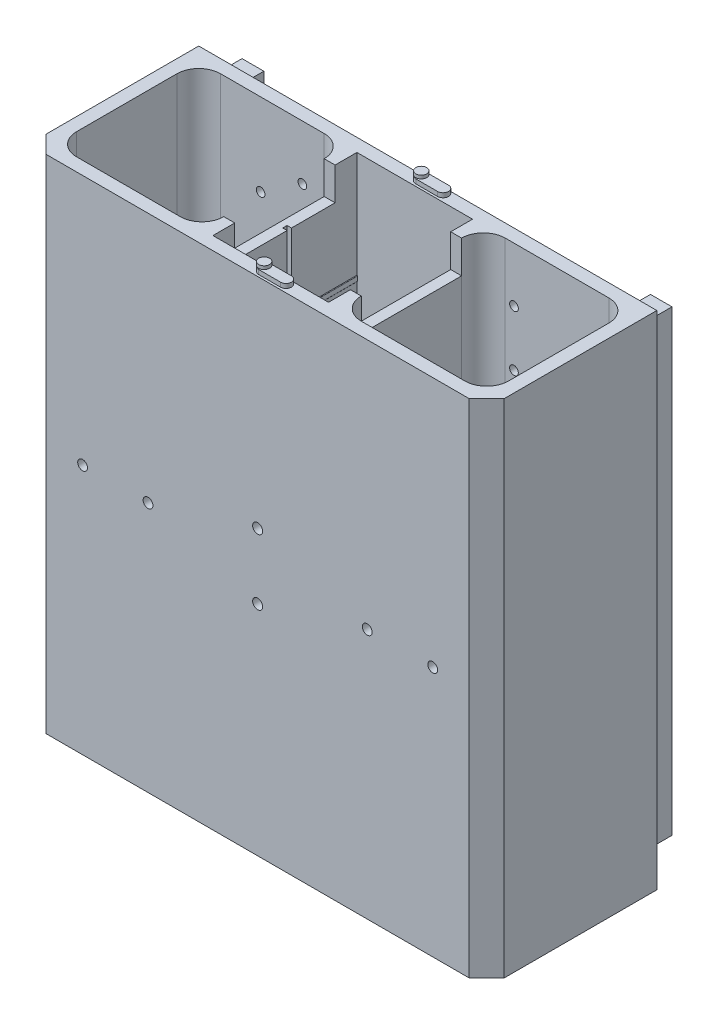
SolidWorks part; units mm, degrees
ref_plane "前视基准面" through (0, 0, 0) normal (0, 0, 1) x (1, 0, 0)
ref_plane "上视基准面" through (0, 0, 0) normal (0, 1, 0) x (1, 0, 0)
ref_plane "右视基准面" through (0, 0, 0) normal (1, 0, 0) x (0, 0, -1)
other "Configuration Table"
sketch "草图1" plane through (0, 0, 0) normal (0, 0, 1) x (1, 0, 0)
  line L1 (0, 0) -> (210, 0)
  line L2 (0, 0) -> (0, 230)
  line L3 (0, 230) -> (210, 230)
  line L4 (210, 0) -> (210, 230)
  line L5 (0, 0) -> (210, 230) construction
  line L6 (0, 230) -> (210, 0) construction
  line L7 (0, 230) -> (26, 230)
  line L8 (0, 230) -> (0, 0)
  line L9 (0, 0) -> (26, 0)
  point P4 (105, 115)
  point P8 (13, 115)
  dimension "D1" = 230
  dimension "D2" = 210
extrude "凸台-拉伸1" add sketch "草图1" along normal blind 6 contours L1 L4 L3 L2
sketch "草图2" plane through (0, 0, 0) normal (0, 0, -1) x (-1, 0, 0)
  line L0 (0, 230) -> (-210, 230) construction
  line L1 (0, 0) -> (-210, 0) construction
  line L2 (-210, 230) -> (-184, 230)
  line L3 (-210, 230) -> (-210, 0)
  line L4 (-210, 0) -> (-184, 0)
  line L5 (-184, 230) -> (-184, 0) construction
  line L6 (-210, 230) -> (-184, 0) construction
  line L7 (-210, 0) -> (-184, 230) construction
  line L9 (0, 230) -> (-20, 230)
  line L10 (0, 230) -> (0, 0)
  line L11 (0, 0) -> (-20, 0)
  line L13 (0, 230) -> (-20, 0) construction
  line L14 (0, 0) -> (-20, 230) construction
  line L15 (-201.925, 219.925) -> (-192.075, 219.925)
  line L16 (-201.925, 219.925) -> (-201.925, 10.075)
  line L17 (-201.925, 10.075) -> (-192.075, 10.075)
  line L18 (-192.075, 219.925) -> (-192.075, 10.075)
  line L19 (-201.925, 219.925) -> (-192.075, 10.075) construction
  line L20 (-201.925, 10.075) -> (-192.075, 219.925) construction
  line L21 (-14.85, 219.925) -> (-4.85, 219.925)
  line L22 (-14.85, 219.925) -> (-14.85, 10.075)
  line L23 (-14.85, 10.075) -> (-4.85, 10.075)
  line L24 (-4.85, 219.925) -> (-4.85, 10.075)
  line L25 (-14.85, 219.925) -> (-4.85, 10.075) construction
  line L26 (-14.85, 10.075) -> (-4.85, 219.925) construction
  point P6 (-197, 115)
  point P18 (-197, 115)
  point P23 (-9.85, 115)
  dimension "D1" = 26
  dimension "D2" = 20
  dimension "D3" = 209.85
  dimension "D4" = 9.85
  dimension "D5" = 13
  dimension "D6" = 115
  dimension "D7" = 209.85
  dimension "D8" = 115
  dimension "D9" = 9.85
  dimension "D10" = 10
extrude "凸台-拉伸3" add sketch "草图2" along normal blind 15 contours L18 L15 L16 L17 | L24 L21 L22 L23
sketch "草图3" plane through (0, 0, 0) normal (0, 0, -1) x (-1, 0, 0)
  line L0 (0, 0) -> (-210, 0) construction
  line L1 (-210, 230) -> (-184, 230)
  line L2 (-210, 230) -> (-210, 0)
  line L3 (-210, 0) -> (-184, 0)
  line L4 (-184, 230) -> (-184, 0)
  line L5 (-210, 230) -> (-184, 0) construction
  line L6 (-210, 0) -> (-184, 230) construction
  line L7 (-210, 115) -> (119.2636, 115) construction
  line L8 (0, 230) -> (-20, 230)
  line L9 (0, 230) -> (0, 0)
  line L10 (0, 0) -> (-20, 0)
  line L11 (-20, 230) -> (-20, 0)
  line L12 (0, 230) -> (-20, 0) construction
  line L13 (0, 0) -> (-20, 230) construction
  line L14 (-105, 230) -> (-105, 0) construction
  circle A0 centre (-169.6426, 192.25) radius 2
  circle A1 centre (-150.5, 205) radius 2
  circle A2 centre (-150.5, 179.5) radius 2
  circle A3 centre (-150.5, 50.5) radius 2
  circle A4 centre (-150.5, 25) radius 2
  circle A5 centre (-169.6426, 37.75) radius 2
  circle A6 centre (-34.3574, 192.25) radius 2
  circle A7 centre (-53.5, 205) radius 2
  circle A8 centre (-53.5, 179.5) radius 2
  circle A9 centre (-53.5, 50.5) radius 2
  circle A10 centre (-53.5, 25) radius 2
  circle A11 centre (-34.3574, 37.75) radius 2
  point P4 (-197, 115)
  point P12 (-10, 115)
  dimension "D8" = 4
  dimension "D9" = 4
  dimension "D10" = 4
  dimension "D12" = 4
  dimension "D13" = 4
  dimension "D14" = 4
  dimension "D1" = 26
  dimension "D2" = 20
  dimension "D3" = 25.5
  dimension "D4" = 23
  dimension "D5" = 23
  dimension "D6" = 33.5
  dimension "D7" = 33.5
  dimension "D11" = 90
  dimension "D15" = 25.5
  dimension "D16" = 23
  dimension "D17" = 23
  dimension "D18" = 33.5
  dimension "D19" = 33.5
  dimension "D20" = 90
extrude "切除-拉伸1" cut sketch "草图3" against normal blind 10 contours A10 | A11 | A9 | A6 | A8 | A7 | A1 | A2 | A0 | A4 | A3 | A5
chamfer "倒角1" [suppressed] distance 10 angle 45
sketch "草图5" [suppressed] plane through (0, 0, 0) normal (0, 0, -1) x (-1, 0, 0)
  line L0 (-172.5, 115) -> (-135, 115) construction
  line L1 (-10, 230) -> (-200, 230) construction
  line L2 (-210, 10) -> (-210, 220) construction
  line L5 (-210, 220) -> (-210, 0)
  line L8 (-75, 115) -> (-37.5, 115) construction
  line L9 (-210, 0) -> (-184, 220) construction
  line L10 (0, 10) -> (0, 220) construction
  circle A0 centre (-172.5, 115) radius 2.5
  circle A1 centre (-135, 115) radius 2.5
  circle A2 centre (-75, 115) radius 2.5
  circle A3 centre (-37.5, 115) radius 2.5
  point P12 (-197, 110)
  dimension "D3" = 5
  dimension "D4" = 5
  dimension "D8" = 5
  dimension "D9" = 5
  dimension "D1" = 37.5
  dimension "D2" = 115
  dimension "D5" = 75
  dimension "D6" = 26
  dimension "D7" = 37.5
  dimension "D10" = 115
  dimension "D11" = 75
extrude "切除-拉伸2" [suppressed] cut sketch "草图5" against normal blind 10 contours A0 | A1 | A3 | A2
sketch "草图6" plane through (0, 0, 6) normal (0, 0, 1) x (1, 0, 0)
  line L0 (105, 230) -> (105, 0) construction
  line L3 (0, 115) -> (210, 115) construction
  line L6 (86.25, 115) -> (123.75, 115) construction
  line L7 (105, 133.75) -> (105, 96.25) construction
  circle A2 centre (105, 133.75) radius 2.5
  circle A3 centre (105, 96.25) radius 2.5
  point P7 (105, 115)
  point P11 (105, 115)
  dimension "D1" = 37.5
  dimension "D2" = 5
  dimension "D3" = 5
extrude "切除-拉伸3" [suppressed] cut sketch "草图6" against normal blind 10
sketch "草图7" [suppressed] plane through (0, 0, 18) normal (0, 0, 1) x (1, 0, 0)
  line L0 (0, 0) -> (210, 0) construction
  line L1 (0, 230) -> (6, 230)
  line L2 (0, 230) -> (0, 0)
  line L3 (0, 0) -> (6, 0)
  line L4 (6, 230) -> (6, 0)
  line L5 (0, 230) -> (6, 0) construction
  line L6 (0, 0) -> (6, 230) construction
  point P4 (3, 115)
  dimension "D1" = 6
extrude "凸台-拉伸4" [suppressed] add sketch "草图7" along normal blind 55
sketch "草图8" [suppressed] plane through (0, 0, 18) normal (0, 0, 1) x (1, 0, 0)
  line L0 (0, 0) -> (210, 0) construction
  line L1 (210, 230) -> (200.2731, 230)
  line L2 (210, 230) -> (210, 0)
  line L3 (210, 0) -> (200.2731, 0)
  line L4 (200.2731, 230) -> (200.2731, 0)
  line L5 (210, 230) -> (200.2731, 0) construction
  line L6 (210, 0) -> (200.2731, 230) construction
  point P4 (205.1365, 115)
  dimension "D1" = 9.7269
sketch "草图17" plane through (0, 0, 6) normal (0, 0, 1) x (1, 0, 0)
  line L0 (0, 0) -> (210, 0) construction
  line L1 (0, 230) -> (6, 230)
  line L2 (0, 230) -> (0, 0)
  line L3 (0, 0) -> (6, 0)
  line L4 (6, 230) -> (6, 0)
  line L5 (0, 230) -> (6, 0) construction
  line L6 (0, 0) -> (6, 230) construction
  line L8 (210, 230) -> (204, 230)
  line L9 (210, 230) -> (210, 0)
  line L10 (210, 0) -> (204, 0)
  line L11 (204, 230) -> (204, 0)
  line L12 (210, 230) -> (204, 0) construction
  line L13 (210, 0) -> (204, 230) construction
  point P4 (3, 115)
  point P12 (207, 115)
  dimension "D1" = 6
  dimension "D2" = 6
extrude "凸台-拉伸9" add sketch "草图17" along normal blind 66
ref_plane "基准面2" through (0, 0, 72) normal (0, 0, 1) x (1, 0, 0)
sketch "草图18" plane through (0, 0, 72) normal (0, 0, 1) x (1, 0, 0)
  line L0 (210, 230) -> (204, 230) construction
  line L1 (210, 0) -> (210, 230) construction
  line L2 (204, 0) -> (210, 0) construction
  line L3 (6, 0) -> (204, 0) construction
  line L4 (0, 0) -> (6, 0) construction
  line L5 (0, 230) -> (0, 0) construction
  line L6 (6, 230) -> (0, 230) construction
  line L7 (6, 230) -> (204, 230) construction
  line L8 (210, 230) -> (204, 230)
  line L9 (210, 0) -> (210, 230)
  line L10 (204, 0) -> (210, 0)
  line L11 (6, 0) -> (204, 0)
  line L12 (0, 0) -> (6, 0)
  line L13 (0, 230) -> (0, 0)
  line L14 (6, 230) -> (0, 230)
  line L15 (6, 230) -> (204, 230)
extrude "凸台-拉伸10" add sketch "草图18" along normal blind 6
chamfer "倒角3" distance 8 angle 45 2 edges at (0, 115, 78) (210, 115, 78)
sketch "草图19" plane through (0, 0, 72) normal (0, 0, -1) x (-1, 0, 0)
  line L0 (-105, 230) -> (-105, 0) construction
  line L2 (-131.5, 230) -> (-136.5, 230)
  line L3 (0, 230) -> (-210, 230) construction
  line L4 (0, 0) -> (-210, 0) construction
  line L5 (-131.5, 230) -> (-131.5, 0)
  line L6 (-131.5, 230) -> (-78.5, 230)
  line L7 (-131.5, 230) -> (-131.5, 0)
  line L8 (-131.5, 0) -> (-78.5, 0)
  line L9 (-78.5, 230) -> (-78.5, 0)
  line L10 (-131.5, 230) -> (-78.5, 0) construction
  line L11 (-131.5, 0) -> (-78.5, 230) construction
  line L12 (-131.5, 0) -> (-136.5, 0)
  line L13 (-136.5, 230) -> (-136.5, 0)
  line L14 (-131.5, 230) -> (-136.5, 0) construction
  line L15 (-131.5, 0) -> (-136.5, 230) construction
  line L16 (-78.5, 230) -> (-73.5, 230)
  line L17 (-78.5, 230) -> (-78.5, 0)
  line L18 (-78.5, 0) -> (-73.5, 0)
  line L19 (-73.5, 230) -> (-73.5, 0)
  line L20 (-78.5, 230) -> (-73.5, 0) construction
  line L21 (-78.5, 0) -> (-73.5, 230) construction
  point P10 (-105, 115)
  point P13 (-134, 115)
  point P16 (-76, 115)
  dimension "D1" = 53
  dimension "D2" = 0
  dimension "D3" = 5
  dimension "D4" = 5
extrude "凸台-拉伸11" add sketch "草图19" along normal blind 66 contours L19 L7 L9 L4 | L7 L13 L4 L5
fillet "圆角4" radius 10 8 edges at (136.5, 115, 72) (136.5, 115, 6) (204, 115, 6) (204, 115, 72) (73.5, 115, 6) (73.5, 115, 72) (6, 115, 6) (6, 115, 72)
sketch "草图21" plane through (0, 0, 72) normal (0, 0, 1) x (1, 0, 0)
  line L0 (8, 115) -> (202, 115) construction
  line L1 (8, 230) -> (8, 0) construction
  line L2 (202, 0) -> (202, 230) construction
  line L3 (105, 230) -> (105, 0) construction
  line L4 (202, 230) -> (8, 230) construction
  line L5 (8, 0) -> (202, 0) construction
  line L6 (105, 130) -> (105, 100) construction
  circle A0 centre (105, 130) radius 2.3
  circle A1 centre (105, 100) radius 2.3
  point P14 (105, 115)
  dimension "D3" = 4.6
  dimension "D4" = 4.6
  dimension "D1" = 0
  dimension "D2" = 30
extrude "切除-拉伸9" cut sketch "草图21" along normal blind 6 contours A1 | A0
sketch "草图23" plane through (78.5, 0, 0) normal (1, 0, 0) x (0, 0, -1)
  line L0 (-6, 80) -> (-70, 80)
  line L1 (-6, 230) -> (-70, 230) construction
  line L2 (-6, 230) -> (-6, 0) construction
  line L3 (-6, 0) -> (-70, 0) construction
  line L4 (-70, 230) -> (-70, 0) construction
  line L5 (-6, 230) -> (-70, 0) construction
  line L6 (-6, 0) -> (-70, 230) construction
  line L7 (-6, 230) -> (-70, 230)
  line L8 (-6, 230) -> (-6, 40)
  line L9 (-6, 40) -> (-70, 40)
  line L10 (-70, 230) -> (-70, 40)
  line L11 (-6, 230) -> (-70, 40) construction
  line L12 (-6, 40) -> (-70, 230) construction
  point P4 (-38, 115)
  point P9 (-38, 135)
  dimension "D1" = 190
  dimension "D2" = 40
sketch "草图24" plane through (0, 0, 6) normal (0, 0, 1) x (1, 0, 0)
  line L0 (78.5, 80.5) -> (78.5, 79.5) construction
  line L1 (78.5, 230) -> (78.5, 40) construction
  line L2 (80, 80.5) -> (80, 79.5)
  line L4 (78.5, 82) -> (78.5, 78)
  arc A0 (80, 80.5) -> (78.5, 82) centre (78.5, 80.5) ccw
  arc A1 (78.5, 78) -> (80, 79.5) centre (78.5, 79.5) ccw
  point P0 (78.5, 80)
  point P6 (78.5, 80)
  dimension "D3" = 1.5
  dimension "D4" = 1.5
  dimension "D1" = 0
  dimension "D2" = 1
extrude "凸台-拉伸12" [suppressed] add sketch "草图24" along normal blind 66
ref_plane "基准面3" through (105, 0, 0) normal (-1, 0, 0) x (0, 0, 1)
mirror "镜向1" [suppressed] about plane through (105, 0, 0) normal (-1, 0, 0)
sketch "草图25" plane through (0, 0, 72) normal (0, 0, -1) x (-1, 0, 0)
  line L8 (-131.5, 230) -> (-131.5, 0)
  line L11 (-131.5, 0) -> (-78.5, 0)
  line L12 (-78.5, 0) -> (-78.5, 230)
  line L15 (-78.5, 230) -> (-131.5, 230)
  line L16 (-131.5, 230) -> (-131.5, 0)
  line L19 (-131.5, 0) -> (-78.5, 0)
  line L20 (-78.5, 0) -> (-78.5, 230)
  line L23 (-78.5, 230) -> (-131.5, 230)
  dimension "D1" = 0
sketch "草图26" plane through (0, 0, 72) normal (0, 0, -1) x (-1, 0, 0)
  line L0 (-131.5, 181) -> (-131.5, 179) construction
  line L1 (-131.5, 230) -> (-131.5, 0) construction
  line L2 (-131.26, 181) -> (-131.26, 179)
  line L3 (-131.74, 181) -> (-131.74, 179)
  line L4 (-78.5, 230) -> (-131.5, 230) construction
  line L5 (-131.5, 230) -> (-131.5, 0) construction
  line L6 (-78.5, 230) -> (-131.5, 230) construction
  line L7 (-131.5, 22.5) -> (-131.5, 20.5) construction
  line L8 (-131.26, 22.5) -> (-131.26, 20.5)
  line L9 (-131.74, 22.5) -> (-131.74, 20.5)
  arc A0 (-131.26, 181) -> (-131.74, 181) centre (-131.5, 181) ccw
  arc A1 (-131.74, 179) -> (-131.26, 179) centre (-131.5, 179) ccw
  arc A2 (-131.26, 22.5) -> (-131.74, 22.5) centre (-131.5, 22.5) ccw
  arc A3 (-131.74, 20.5) -> (-131.26, 20.5) centre (-131.5, 20.5) ccw
  point P4 (-131.5, 180)
  point P14 (-131.5, 21.5)
  dimension "D1" = 0.24
  dimension "D2" = 2
  dimension "D3" = 50
  dimension "D4" = 2
extrude "凸台-拉伸13" add sketch "草图26" along normal blind 66
mirror "镜向2" about plane through (105, 0, 0) normal (-1, 0, 0) of "凸台-拉伸13"
sketch "草图28" plane through (0, 0, 72) normal (0, 0, -1) x (-1, 0, 0)
  line L0 (-78.5, 230) -> (-131.5, 230) construction
  line L1 (-78.5, 230) -> (-131.5, 230) construction
  line L2 (-131.5, 230) -> (-131.5, 0) construction
  line L3 (-131.5, 11.46) -> (-78.5, 11.46)
  line L4 (-131.5, 11.46) -> (-131.5, 8.46)
  line L5 (-131.5, 8.46) -> (-78.5, 8.46)
  line L6 (-78.5, 11.46) -> (-78.5, 8.46)
  line L7 (-131.5, 11.46) -> (-78.5, 8.46) construction
  line L8 (-131.5, 8.46) -> (-78.5, 11.46) construction
  line L9 (-78.5, 230) -> (-78.5, 0) construction
  point P6 (-105, 9.96)
  point P11 (-78.5, 20.2624)
  dimension "D1" = 218.54
  dimension "D2" = 3
extrude "凸台-拉伸14" add sketch "草图28" along normal blind 66
sketch "草图30" plane through (0, 230, 0) normal (0, 1, 0) x (1, 0, 0)
  line L0 (78.5, -6) -> (131.5, -6) construction
  line L1 (78.5, -6) -> (131.5, -6) construction
  line L2 (78.5, -6) -> (78.5, -70) construction
  line L3 (78.5, -36) -> (76.5, -36)
  line L4 (78.5, -36) -> (78.5, -38)
  line L5 (78.5, -38) -> (76.5, -38)
  line L6 (76.5, -36) -> (76.5, -38)
  line L7 (78.5, -36) -> (76.5, -38) construction
  line L8 (78.5, -38) -> (76.5, -36) construction
  point P6 (77.5, -37)
  dimension "D1" = 2
  dimension "D2" = 30
  dimension "D3" = 2
extrude "切除-拉伸10" cut sketch "草图30" against normal blind 35
sketch "草图31" plane through (0, 8.46, 0) normal (0, -1, 0) x (1, 0, 0)
  line L0 (105, 72) -> (105, 6) construction
  line L1 (105, 16.2) -> (117.5, 16.2) construction
  line L2 (98, 23.2) -> (112, 23.2)
  line L3 (98, 23.2) -> (98, 9.2)
  line L4 (131.5, 72) -> (78.5, 72)
  line L5 (78.5, 72) -> (78.5, 6)
  line L6 (78.5, 6) -> (131.5, 6)
  line L7 (131.5, 6) -> (131.5, 72)
  line L8 (131.5, 72) -> (78.5, 72) construction
  line L9 (78.5, 72) -> (78.5, 6) construction
  line L10 (78.5, 6) -> (131.5, 6) construction
  line L11 (131.5, 6) -> (131.5, 72) construction
  line L12 (98, 9.2) -> (112, 9.2)
  line L13 (112, 23.2) -> (112, 9.2)
  line L14 (98, 23.2) -> (112, 9.2) construction
  line L15 (98, 9.2) -> (112, 23.2) construction
  circle A0 centre (92.7, 16.2) radius 1.35
  circle A1 centre (117.3, 16.2) radius 1.35
  point P10 (105, 16.2)
  dimension "D8" = 2.7
  dimension "D9" = 2.7
  dimension "D2" = 14
  dimension "D3" = 14
  dimension "D4" = 12.3
  dimension "D5" = 12.3
  dimension "D6" = 3.2
  dimension "D7" = 0
  dimension "D1" = 0
extrude "切除-拉伸11" cut sketch "草图31" against normal through all
sketch "草图32" plane through (0, 0, 6) normal (0, 0, 1) x (1, 0, 0)
  line L0 (131.5, 8.46) -> (78.5, 8.46) construction
  line L1 (119.5, 8.46) -> (131.5, 8.46)
  line L2 (119.5, 8.46) -> (119.5, -1.54)
  line L3 (119.5, -1.54) -> (131.5, -1.54)
  line L4 (131.5, 8.46) -> (131.5, -1.54)
  line L5 (119.5, 8.46) -> (131.5, -1.54) construction
  line L6 (119.5, -1.54) -> (131.5, 8.46) construction
  line L7 (131.5, 8.46) -> (78.5, 8.46) construction
  line L8 (131.5, 8.46) -> (131.5, 0) construction
  line L9 (131.5, 8.46) -> (131.5, 0) construction
  line L10 (78.5, 0) -> (131.5, 0) construction
  line L11 (78.5, 0) -> (131.5, 0) construction
  point P4 (125.5, 3.46)
  dimension "D1" = 10
  dimension "D2" = 0
  dimension "D3" = 0
  dimension "D4" = 12
extrude "切除-拉伸12" cut sketch "草图32" against normal through all
sketch "草图33" plane through (131.5, 0, 0) normal (-1, 0, 0) x (0, 0, 1)
  line L0 (0, 8.46) -> (72, 8.46) construction
  line L1 (30, 8.46) -> (50, 8.46)
  line L2 (30, 8.46) -> (30, 0)
  line L3 (30, 0) -> (50, 0)
  line L4 (50, 8.46) -> (50, 0)
  line L5 (30, 8.46) -> (50, 0) construction
  line L6 (30, 0) -> (50, 8.46) construction
  line L7 (0, 0) -> (72, 0) construction
  line L8 (0, 0) -> (0, 8.46) construction
  point P4 (40, 4.23)
  point P9 (30, 4.23)
  dimension "D1" = 20
  dimension "D2" = 30
extrude "切除-拉伸13" cut sketch "草图33" against normal up to next
sketch "草图34" plane through (0, 0, 72) normal (0, 0, -1) x (-1, 0, 0)
  line L0 (-170.25, 230) -> (-170.25, 0) construction
  line L1 (-194, 115) -> (-146.5, 115) construction
  line L2 (-185.25, 115) -> (-155.25, 115)
  line L4 (-194, 0) -> (-146.5, 0)
  line L19 (-194, 0) -> (-146.5, 0)
  line L23 (-146.5, 0) -> (-146.5, 230)
  line L25 (-146.5, 0) -> (-146.5, 230)
  line L27 (-146.5, 230) -> (-194, 230)
  line L28 (-146.5, 230) -> (-194, 230)
  line L29 (-194, 230) -> (-194, 0)
  line L30 (-194, 230) -> (-194, 0)
  circle A0 centre (-185.25, 115) radius 2.25
  circle A1 centre (-155.25, 115) radius 2.25
  point P12 (-170.25, 115)
  dimension "D2" = 4.5
  dimension "D3" = 4.5
  dimension "D4" = 30
  dimension "D1" = 0
extrude "切除-拉伸14" cut sketch "草图34" against normal blind 30 contours A0 | A1
sketch "草图36" plane through (0, 0, 72) normal (0, 0, -1) x (-1, 0, 0)
  line L0 (-39.75, 230) -> (-39.75, 0) construction
  line L1 (-63.5, 115) -> (-16, 115) construction
  line L2 (-54.75, 115) -> (-24.75, 115)
  line L4 (-16, 230) -> (-63.5, 230)
  line L19 (-16, 230) -> (-63.5, 230)
  line L23 (-63.5, 230) -> (-63.5, 0)
  line L25 (-63.5, 230) -> (-63.5, 0)
  line L27 (-63.5, 0) -> (-16, 0)
  line L28 (-63.5, 0) -> (-16, 0)
  line L29 (-16, 0) -> (-16, 230)
  line L30 (-16, 0) -> (-16, 230)
  circle A0 centre (-54.75, 115) radius 2.25
  circle A1 centre (-24.75, 115) radius 2.25
  point P12 (-39.75, 115)
  dimension "D2" = 4.5
  dimension "D3" = 4.5
  dimension "D4" = 30
  dimension "D1" = 0
extrude "切除-拉伸15" cut sketch "草图36" against normal blind 30
sketch "草图37" plane through (0, 0, 72) normal (0, 0, -1) x (-1, 0, 0)
  line L12 (-131.5, 11.46) -> (-78.5, 11.46)
  line L13 (-78.5, 11.46) -> (-78.5, 20.26)
  line L14 (-78.74, 20.5) -> (-78.74, 22.5)
  line L15 (-78.5, 22.74) -> (-78.5, 178.76)
  line L16 (-78.74, 179) -> (-78.74, 181)
  line L17 (-78.5, 181.24) -> (-78.5, 230)
  line L18 (-78.5, 230) -> (-131.5, 230)
  line L19 (-131.5, 230) -> (-131.5, 181.24)
  line L20 (-131.26, 181) -> (-131.26, 179)
  line L21 (-131.5, 178.76) -> (-131.5, 22.74)
  line L22 (-131.26, 22.5) -> (-131.26, 20.5)
  line L23 (-131.5, 20.26) -> (-131.5, 11.46)
  line L25 (-78.5, 11.46) -> (-78.5, 20.26)
  line L26 (-78.74, 20.5) -> (-78.74, 22.5)
  line L27 (-78.5, 22.74) -> (-78.5, 178.76)
  line L28 (-78.74, 179) -> (-78.74, 181)
  line L29 (-78.5, 181.24) -> (-78.5, 230)
  line L30 (-78.5, 230) -> (-131.5, 230)
  line L31 (-131.5, 230) -> (-131.5, 181.24)
  line L32 (-131.26, 181) -> (-131.26, 179)
  line L33 (-131.5, 178.76) -> (-131.5, 22.74)
  line L34 (-131.26, 22.5) -> (-131.26, 20.5)
  line L35 (-131.5, 20.26) -> (-131.5, 11.46)
  line L41 (-131.5, 11.46) -> (-78.5, 11.46)
  circle A1 centre (-105, 130) radius 2.3
  circle A2 centre (-105, 130) radius 2.3
  circle A3 centre (-105, 100) radius 2.3
  circle A4 centre (-105, 100) radius 2.3
  arc A8 (-78.74, 20.5) -> (-78.5, 20.26) centre (-78.5, 20.5) ccw
  arc A9 (-78.5, 22.74) -> (-78.74, 22.5) centre (-78.5, 22.5) ccw
  arc A10 (-78.74, 179) -> (-78.5, 178.76) centre (-78.5, 179) ccw
  arc A11 (-78.5, 181.24) -> (-78.74, 181) centre (-78.5, 181) ccw
  arc A12 (-131.26, 181) -> (-131.5, 181.24) centre (-131.5, 181) ccw
  arc A13 (-131.5, 178.76) -> (-131.26, 179) centre (-131.5, 179) ccw
  arc A14 (-131.26, 22.5) -> (-131.5, 22.74) centre (-131.5, 22.5) ccw
  arc A15 (-131.5, 20.26) -> (-131.26, 20.5) centre (-131.5, 20.5) ccw
  arc A16 (-78.74, 20.5) -> (-78.5, 20.26) centre (-78.5, 20.5) ccw
  arc A17 (-78.5, 22.74) -> (-78.74, 22.5) centre (-78.5, 22.5) ccw
  arc A18 (-78.74, 179) -> (-78.5, 178.76) centre (-78.5, 179) ccw
  arc A19 (-78.5, 181.24) -> (-78.74, 181) centre (-78.5, 181) ccw
  arc A20 (-131.26, 181) -> (-131.5, 181.24) centre (-131.5, 181) ccw
  arc A21 (-131.5, 178.76) -> (-131.26, 179) centre (-131.5, 179) ccw
  arc A22 (-131.26, 22.5) -> (-131.5, 22.74) centre (-131.5, 22.5) ccw
  arc A23 (-131.5, 20.26) -> (-131.26, 20.5) centre (-131.5, 20.5) ccw
  dimension "D1" = 0
  dimension "D2" = 0
  dimension "D3" = 0
extrude "凸台-拉伸15" [suppressed] add sketch "草图37" along normal blind 4
sketch "草图39" plane through (73.5, 0, 0) normal (-1, 0, 0) x (0, 0, 1)
  line L1 (16, 230) -> (62, 230)
  line L2 (16, 230) -> (16, 215)
  line L3 (16, 215) -> (62, 215)
  line L4 (62, 230) -> (16, 230)
  line L5 (16, 230) -> (16, 0)
  line L6 (16, 0) -> (62, 0)
  line L7 (16, 230) -> (16, 0)
  line L8 (62, 230) -> (16, 230)
  line L10 (16, 0) -> (62, 0)
  line L12 (62, 230) -> (62, 215)
  line L13 (16, 230) -> (62, 215) construction
  line L14 (16, 215) -> (62, 230) construction
  line L18 (62, 0) -> (62, 230)
  line L19 (62, 0) -> (62, 230)
  point P6 (39, 222.5)
  line M6 (62, 230) -> (16, 230)
  line M7 (16, 230) -> (16, 0)
  line M9 (62, 0) -> (62, 230)
  dimension "D2" = 15
  dimension "D1" = 0
extrude "切除-拉伸16" cut sketch "草图39" against normal blind 104 contours L3 M7 M9 M6
sketch "草图40" plane through (0, 230, 0) normal (0, 1, 0) x (1, 0, 0)
  line L0 (105, 0) -> (105, -6) construction
  line L1 (0, 0) -> (210, 0) construction
  line L2 (78.5, -6) -> (131.5, -6) construction
  circle A0 centre (105, -3) radius 1.5
  dimension "D1" = 3
extrude "凸台-拉伸16" add sketch "草图40" along normal blind 3
sketch "草图41" plane through (0, 233, 0) normal (0, 1, 0) x (1, 0, 0)
  circle A0 centre (105, -3) radius 2.5
  dimension "D1" = 5
extrude "凸台-拉伸17" add sketch "草图41" along normal blind 1.5
sketch "草图42" plane through (0, 230, 0) normal (0, 1, 0) x (1, 0, 0)
  line L6 (0, 0) -> (0, -70)
  line L7 (0, -70) -> (8, -78)
  line L8 (8, -78) -> (202, -78)
  line L9 (202, -78) -> (210, -70)
  line L10 (210, -70) -> (210, 0)
  line L11 (210, 0) -> (0, 0)
  line L12 (0, 0) -> (0, -70)
  line L13 (0, -70) -> (8, -78)
  line L14 (8, -78) -> (202, -78)
  line L15 (202, -78) -> (210, -70)
  line L16 (210, -70) -> (210, 0)
  line L17 (210, 0) -> (0, 0)
  circle A0 centre (105, -3) radius 1.6
  circle A1 centre (105, -3) radius 1.5
  circle A2 centre (105, -3) radius 1.5 construction
  dimension "D3" = 3.2
  dimension "D1" = 0
  dimension "D2" = 0
ref_plane "基准面4" through (0, 230.5, 0) normal (0, 1, 0) x (1, 0, 0)
sketch "草图44" plane through (0, 230.5, 0) normal (0, 1, 0) x (1, 0, 0)
  line L0 (105, -3) -> (115, -3) construction
  line L1 (105, -0.5) -> (115, -0.5)
  line L2 (105, -5.5) -> (115, -5.5)
  arc A2 (105, -0.5) -> (105, -5.5) centre (105, -3) ccw
  arc A3 (115, -5.5) -> (115, -0.5) centre (115, -3) ccw
  circle A4 centre (105, -3) radius 1.62
  point P3 (110, -3)
  point P9 (0, 0)
  point P10 (0, 0)
  dimension "D1" = 2.5
  dimension "D2" = 10
  dimension "D3" = 3.24
extrude "凸台-拉伸19" add sketch "草图44" along normal blind 2 separate body
ref_plane "基准面5" through (0, 0, 39) normal (0, 0, 1) x (1, 0, 0)
mirror "镜向3" about plane through (0, 0, 39) normal (0, 0, 1) of "凸台-拉伸16", "凸台-拉伸17", "凸台-拉伸19"
sketch "草图45" plane through (0, 230, 0) normal (0, 1, 0) x (1, 0, 0)
  line L0 (105, -75) -> (115, -75) construction
  line L1 (105, -72.5) -> (115, -72.5)
  line L2 (105, -77.5) -> (115, -77.5)
  circle A0 centre (105, -75) radius 1.62
  arc A1 (105, -72.5) -> (105, -77.5) centre (105, -75) ccw
  arc A2 (115, -77.5) -> (115, -72.5) centre (115, -75) ccw
  point P3 (110, -75)
  dimension "D1" = 3.24
  dimension "D2" = 2.5
  dimension "D3" = 10
sketch "草图46" plane through (0, 230.5, 0) normal (0, 1, 0) x (1, 0, 0)
  line L2 (115, -72.5) -> (105, -72.5)
  line L3 (105, -77.5) -> (115, -77.5)
  line L4 (115, -72.5) -> (105, -72.5)
  line L5 (105, -77.5) -> (115, -77.5)
  circle A1 centre (105, -75) radius 1.62
  circle A3 centre (105, -75) radius 1.62
  arc A4 (115, -77.5) -> (115, -72.5) centre (115, -75) ccw
  arc A5 (105, -72.5) -> (105, -77.5) centre (105, -75) ccw
  arc A6 (115, -77.5) -> (115, -72.5) centre (115, -75) ccw
  arc A7 (105, -72.5) -> (105, -77.5) centre (105, -75) ccw
  dimension "D1" = 0
  dimension "D2" = 0
extrude "凸台-拉伸20" add sketch "草图46" along normal blind 2 separate body
